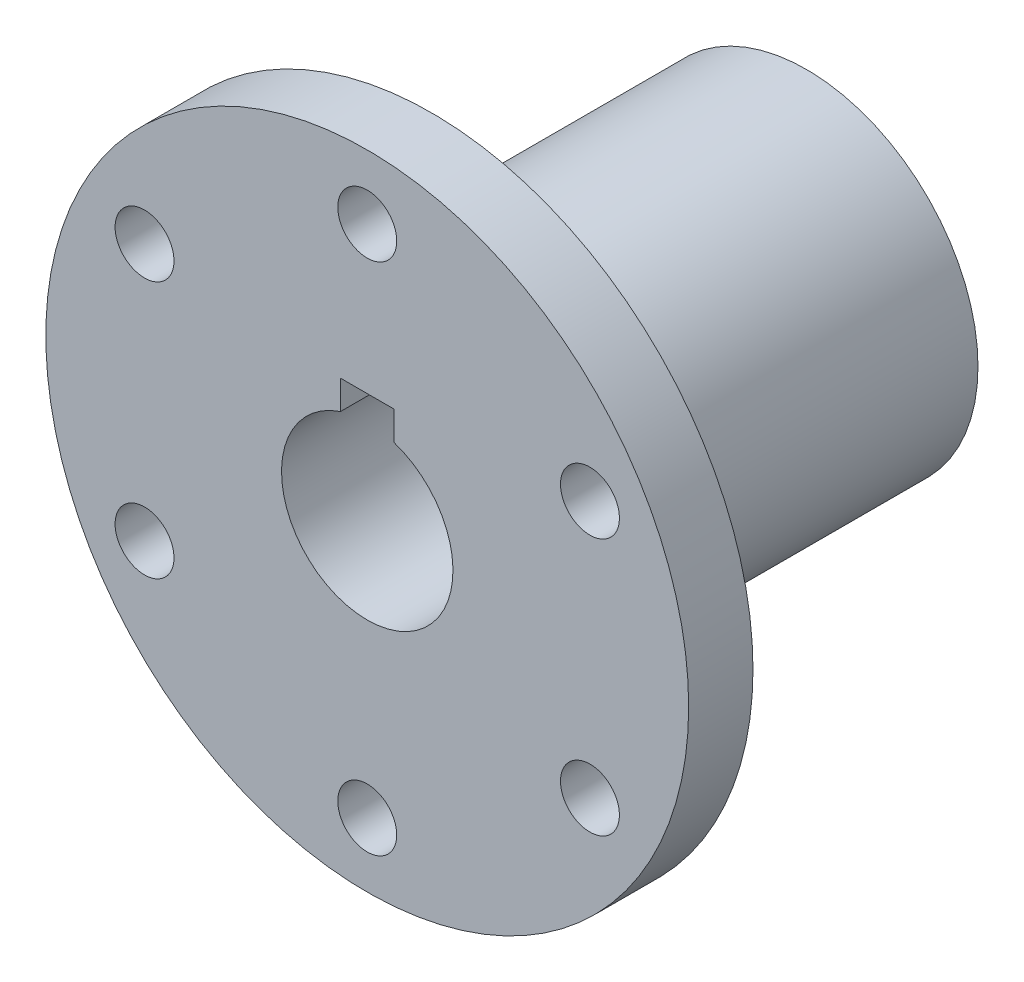
SolidWorks part; units mm, degrees
ref_plane "前视基准面" through (0, 0, 0) normal (0, 0, 1) x (1, 0, 0)
ref_plane "上视基准面" through (0, 0, 0) normal (0, 1, 0) x (1, 0, 0)
ref_plane "右视基准面" through (0, 0, 0) normal (1, 0, 0) x (0, 0, -1)
sketch "草图1" plane through (0, 0, 0) normal (1, 0, 0) x (0, 0, -1)
  line L0 (0, 0) -> (24.59, 0) construction
  line L1 (0, 0) -> (0, 30)
  line L2 (0, 30) -> (6, 30)
  line L3 (6, 30) -> (6, 16)
  line L4 (6, 16) -> (41, 16)
  line L5 (41, 16) -> (41, 0)
  line L6 (41, 0) -> (0, 0)
  dimension "D1" = 0
  dimension "D2" = 30
  dimension "D3" = 6
  dimension "D4" = 16
  dimension "D5" = 35
revolve "旋转1" add sketch "草图1" angle 360 about L0
sketch "草图2" plane through (0, 0, -6) normal (0, 0, -1) x (-1, 0, 0)
  line L0 (0, 0) -> (0, 40.8109) construction
  circle A0 centre (0, 24) radius 2.75
  circle A1 centre (20.7846, 12) radius 2.75
  circle A2 centre (20.7846, -12) radius 2.75
  circle A3 centre (0, -24) radius 2.75
  circle A4 centre (-20.7846, -12) radius 2.75
  circle A5 centre (-20.7846, 12) radius 2.75
  point P17 (0, 0)
  dimension "D1" = 5.5
  dimension "D2" = 24
  dimension "D3" = 6
extrude "切除-拉伸1" cut sketch "草图2" against normal up to next
fillet "圆角1" radius 2 1 edges at (16, 0, -6)
sketch "Sketch1" plane through (0, 0, -41) normal (0, 0, -1) x (-1, 0, 0)
  circle A0 centre (0, 0) radius 8
  dimension "D1" = 16
extrude "Cut-Extrude1" cut sketch "Sketch1" against normal through all
sketch "Sketch2" plane through (0, 0, -41) normal (0, 0, -1) x (-1, 0, 0)
  line L0 (0, 13.9376) -> (0, 0) construction
  line L1 (-2.5, 7.5993) -> (-2.5, 10.3)
  line L2 (-2.5, 10.3) -> (2.5, 10.3)
  line L3 (2.5, 10.3) -> (2.5, 7.5993)
  circle A0 centre (0, 0) radius 8 construction
  arc A1 (-2.5, 7.5993) -> (2.5, 7.5993) centre (0, 0) cw
  point P9 (0, 8)
  dimension "D1" = 5
  dimension "D2" = 2.3
extrude "Cut-Extrude2" cut sketch "Sketch2" against normal through all
